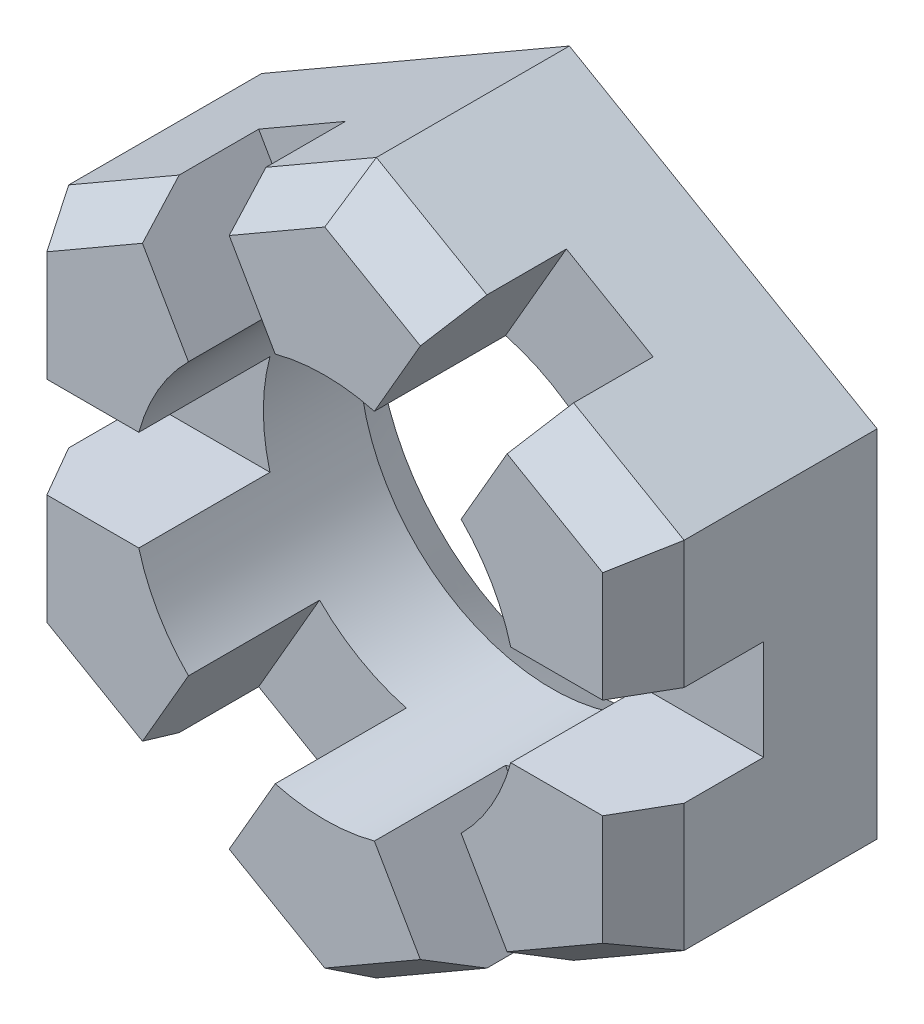
SolidWorks part; units mm, degrees
ref_plane "Plano frontal" through (0, 0, 0) normal (0, 0, 1) x (1, 0, 0)
ref_plane "Plano superior" through (0, 0, 0) normal (0, 1, 0) x (1, 0, 0)
ref_plane "Plano direito" through (0, 0, 0) normal (1, 0, 0) x (0, 0, -1)
sketch "Esboço1" plane through (0, 0, 0) normal (0, 0, 1) x (1, 0, 0)
  line L0 (0, 0) -> (0, 57.176) construction
  line L2 (0, 17.205) -> (-14.9, 8.6025)
  line L3 (-14.9, 8.6025) -> (-14.9, -8.6025)
  line L4 (-14.9, -8.6025) -> (0, -17.205)
  line L5 (0, -17.205) -> (14.9, -8.6025)
  line L6 (14.9, -8.6025) -> (14.9, 8.6025)
  line L7 (14.9, 8.6025) -> (0, 17.205)
  circle A0 centre (0, 0) radius 14.9 construction
extrude "Ressalto-extrusão2" add sketch "Esboço1" along normal blind 13
sketch "Esboço3" plane through (0, 0, 13) normal (0, 0, 1) x (1, 0, 0)
  circle A0 centre (0, 0) radius 9.325
  dimension "D1" = 18.65
extrude "Corte-extrusão1" cut sketch "Esboço3" against normal through all
sketch "Esboço4" plane through (0, 0, 13) normal (0, 0, 1) x (1, 0, 0)
  line L0 (-14.9, 0) -> (14.9, 0) construction
  line L1 (-14.9, 8.6025) -> (-14.9, -8.6025) construction
  line L2 (14.9, -8.6025) -> (14.9, 8.6025) construction
  line L3 (-14.9, 2.425) -> (-14.9, -2.425)
  line L4 (-14.9, 2.425) -> (-6.1537, 2.425)
  line L5 (-6.1537, 2.425) -> (-6.1537, -2.425)
  line L6 (-6.1537, -2.425) -> (-14.9, -2.425)
  line L7 (-5.3499, 14.1163) -> (-9.5501, 11.6913)
  line L8 (-5.3499, 14.1163) -> (-0.9768, 6.5418)
  line L9 (-0.9768, 6.5418) -> (-5.177, 4.1168)
  line L10 (-5.177, 4.1168) -> (-9.5501, 11.6913)
  line L11 (9.5501, 11.6913) -> (5.3499, 14.1163)
  line L12 (9.5501, 11.6913) -> (5.177, 4.1168)
  line L13 (5.177, 4.1168) -> (0.9768, 6.5418)
  line L14 (0.9768, 6.5418) -> (5.3499, 14.1163)
  line L15 (14.9, -2.425) -> (14.9, 2.425)
  line L16 (14.9, -2.425) -> (6.1537, -2.425)
  line L17 (6.1537, -2.425) -> (6.1537, 2.425)
  line L18 (6.1537, 2.425) -> (14.9, 2.425)
  line L19 (5.3499, -14.1163) -> (9.5501, -11.6913)
  line L20 (5.3499, -14.1163) -> (0.9768, -6.5418)
  line L21 (0.9768, -6.5418) -> (5.177, -4.1168)
  line L22 (5.177, -4.1168) -> (9.5501, -11.6913)
  line L23 (-9.5501, -11.6913) -> (-5.3499, -14.1163)
  line L24 (-9.5501, -11.6913) -> (-5.177, -4.1168)
  line L25 (-5.177, -4.1168) -> (-0.9768, -6.5418)
  line L26 (-0.9768, -6.5418) -> (-5.3499, -14.1163)
  dimension "D1" = 6
extrude "Corte-extrusão2" cut sketch "Esboço4" against normal blind 6.35
chamfer "Chanfro1" distance 2.5 angle 30 12 edges at (-2.6749, -15.6607, 13) (2.6749, -15.6607, 13) (12.2251, -10.1469, 13) (14.9, -5.5138, 13) (14.9, 5.5138, 13) (12.2251, 10.1469, 13) (2.6749, 15.6607, 13) (-2.6749, 15.6607, 13) (-12.2251, 10.1469, 13) (-14.9, 5.5138, 13) (-12.2251, -10.1469, 13) (-14.9, -5.5138, 13)
chamfer "Chanfro2" distance 2 angle 30 1 edges at (9.325, 0, 0)
chamfer "Chanfro3" distance 2 angle 30 6 edges at (-7.45, -12.9038, 0) (-14.9, 0, 0) (-7.45, 12.9038, 0) (7.45, 12.9038, 0) (14.9, 0, 0) (7.45, -12.9038, 0)
